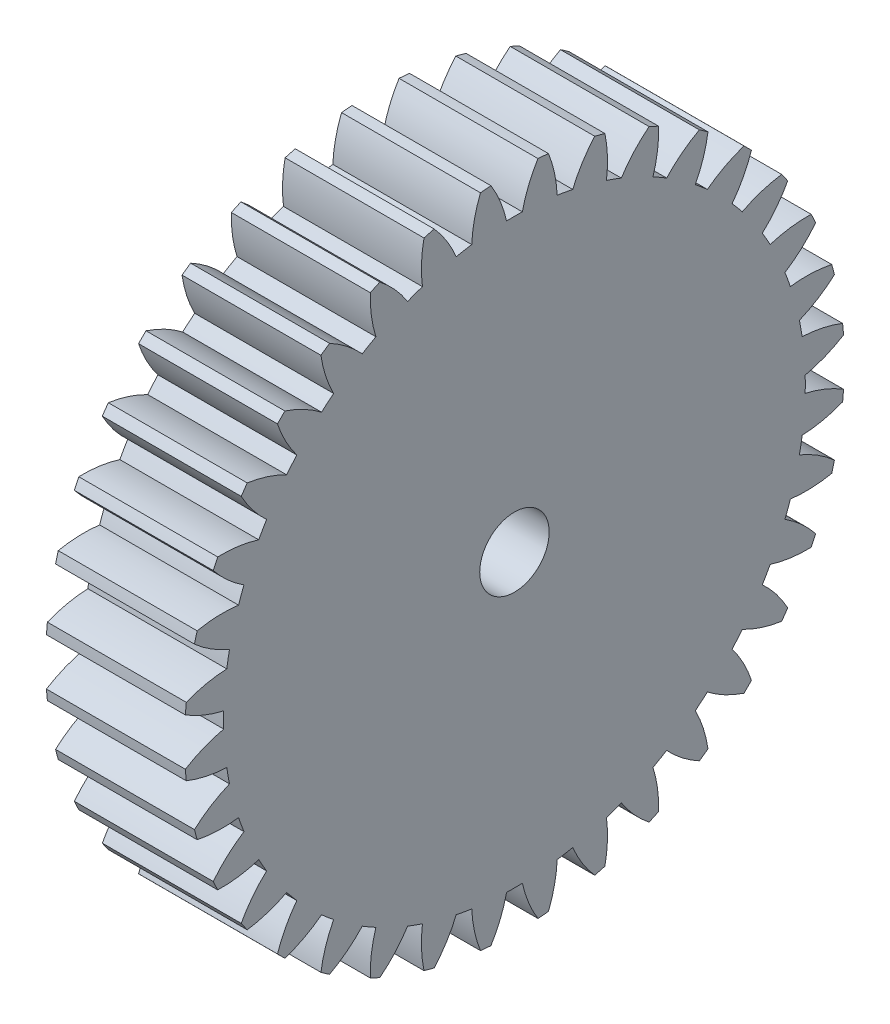
SolidWorks part; units mm, degrees
ref_plane "Plane1" through (0, 0, 0) normal (0, 0, 1) x (1, 0, 0)
ref_plane "Plane2" through (0, 0, 0) normal (0, 1, 0) x (1, 0, 0)
ref_plane "Plane3" through (0, 0, 0) normal (1, 0, 0) x (0, 0, -1)
other "Configuration Table"
sketch "HoldingSke" plane through (0, 0, 0) normal (0, 1, 0) x (1, 0, 0)
  line L0 (0, 0) -> (0.809, -0.5878)
  line L1 (-15, 0) -> (100, 0) construction
  line L2 (0, 0) -> (-2.1039, 2.3779)
  line L3 (0, 0) -> (-11.863, 4.5341)
  line L4 (0, 0) -> (6.9867, 5.0761)
  line L5 (0, 0) -> (-46.8476, -17.4728)
  line L6 (0, 0) -> (-6.6317, -4.4744)
  line L7 (-2.1039, 2.3779) -> (8.6586, 51.2059)
  line L8 (-76.2, 54.61) -> (-75.5, 54.61)
  line L9 (-71.009, 38.7566) -> (-53.1078, 45.2721)
  line L10 (-76.2, 71.12) -> (104.1128, 71.12)
  line L11 (0, 0) -> (-8, 0)
  line L12 (-76.2, 101.6) -> (-76.162, 101.6)
  line L13 (24.9733, 27.94) -> (52.9518, 28.4284)
  line L14 (24.9733, 27.94) -> (24.9743, 27.94)
  line L15 (24.9733, 27.94) -> (100.4006, 29.5858)
  line L16 (-63.627, -1) -> (-12.827, -1)
  circle A0 centre (0, 0) radius 2
  circle A1 centre (0, 0) radius 16.749
  circle A2 centre (0, 0) radius 37.5
  circle A3 centre (0, 0) radius 2
  dimension "MHD" = 33.498
  dimension "Hub_dia" = 75
  dimension "Bore" = 4
  dimension "MBD" = 4
  dimension "Num_teeth" = 36
  dimension "Pitch" = 1
  dimension "Overall_len" = 50
  dimension "Show_teeth" = 36
  dimension "Thickness" = 8
  dimension "OAL" = 50.0001
  dimension "T_dim" = 0.7
  dimension "Ap" = 20
  dimension "H" = 19.05
  dimension "Pitch_radius" = 180.3128
  dimension "Width" = 8
  dimension "Backlash" = 0.038
  dimension "Addendum_fac" = 1
  dimension "Dedendum_fac" = 1.25
  dimension "Clearance_fac" = 0.25
  dimension "Dedendum_add" = 0.001
  dimension "Module" = 1
sketch "BasProSke" plane through (0, 0, 0) normal (0, 1, 0) x (1, 0, 0)
  line L0 (-10, 0) -> (60, 0) construction
  line L1 (0, 0) -> (0, 19)
  line L2 (0, 0) -> (8, 0)
  line L3 (8, 0) -> (8, 19)
  line L4 (8, 19) -> (0, 19)
  dimension "Thickness" = 8
  dimension "Diameter" = 38
revolve "Base-Revolve" add sketch "BasProSke" angle 360 about L0
sketch "TooCutSke" plane through (0, 0, 0) normal (1, 0, 0) x (0, 0, -1)
  line L1 (0, 0) -> (0, 107) construction
  line L2 (0, 0) -> (-0.8516, 17.9798) construction
  line L3 (0, 0) -> (-3.1351, 35.8344) construction
  line L4 (-0.8516, 17.9798) -> (-1.5676, 17.9172) construction
  arc A0 (0.4547, 16.7428) -> (-0.4547, 16.7428) centre (0, 0) ccw
  arc A1 (1.3689, 18.9761) -> (-1.3689, 18.9761) centre (0, 0) ccw
  circle A2 centre (0, 0) radius 18 construction
  circle A3 centre (0, 0) radius 16.9145 construction
  arc A4 (-0.4547, 16.7428) -> (-1.3689, 18.9761) centre (-7.4808, 15.1702) ccw
  arc A5 (1.3689, 18.9761) -> (0.4547, 16.7428) centre (7.4808, 15.1702) ccw
  dimension "Root_dia" = 33.498
  dimension "Overcut_dia" = 38.0508
  dimension "Pitch_dia" = 36
  dimension "Base_dia" = 33.8289
  dimension "Flank_rad" = 7.2
  dimension "Half_ang" = 5
  dimension "Half_CT" = 0.7186
extrude "ToothCut" cut sketch "TooCutSke" along normal through all
fillet "Breaks" [suppressed] radius 0.02
fillet "RootFillets" [suppressed] radius 0.251
pattern_circular "TeethCuts" count 36 every 10 about axis through (-10, 0, 0) along (1, 0, 0) of "ToothCut", "RootFillets", "Breaks"
sketch "HubNeaOneSke" plane through (0, 0, 0) normal (-1, 0, 0) x (0, 0, 1)
  circle A0 centre (0, 0) radius 16.749
  dimension "Diameter" = 33.498
extrude "HubNearOne" [suppressed] add sketch "HubNeaOneSke" along normal blind 42.0001
sketch "HubNeaBotSke" plane through (0, 0, 0) normal (-1, 0, 0) x (0, 0, 1)
  circle A0 centre (0, 0) radius 16.749
  dimension "Diameter" = 33.498
extrude "HubNearBoth" [suppressed] add sketch "HubNeaBotSke" along normal blind 21
ref_plane "FarPln" through (8, 0, 0) normal (1, 0, 0) x (0, 0, -1)
sketch "HubFarSke" plane through (8, 0, 0) normal (1, 0, 0) x (0, 0, -1)
  circle A0 centre (0, 0) radius 16.749
  dimension "Diameter" = 33.498
extrude "HubFar" [suppressed] add sketch "HubFarSke" along normal blind 21
sketch "BorSke" plane through (0, 0, 0) normal (1, 0, 0) x (0, 0, -1)
  circle A0 centre (0, 0) radius 2
  dimension "Diameter" = 4
extrude "Bore" cut sketch "BorSke" along normal mid plane 100.0001
sketch "KeySke" plane through (0, 0, 0) normal (1, 0, 0) x (0, 0, -1)
  line L0 (-0.8, 0) -> (-0.8, 2.7)
  line L1 (-0.8, 2.7) -> (0.8, 2.7)
  line L2 (0.8, 2.7) -> (0.8, 0)
  line L3 (0, 0) -> (0, 34) construction
  line L4 (-0.8, 0) -> (0.8, 0)
  dimension "Offset" = 2.7
  dimension "Width" = 1.6
extrude "Keyway" [suppressed] cut sketch "KeySke" along normal mid plane 100.0001
pattern_circular "Keyway2" [suppressed] count 2 every 90 about axis through (-10, 0, 0) along (1, 0, 0)
equation "' \"Module@HoldingSke\" = 6.35"
equation "' \"Num_teeth@HoldingSke\" = 12"
equation "' \"Ap@HoldingSke\" =  20"
equation "' \"Ap@HoldingSke\" = 20"
equation "' \"Width@HoldingSke\" = 0.5 * 25.4"
equation "' \"Hub_dia@HoldingSke\"= 1 * 25.4"
equation "' \"Hub_dia@HoldingSke\" = 1 * 25.4"
equation "' \"Overall_len@HoldingSke\" = 1.0 * 25.4"
equation "' \"Bore@HoldingSke\" = 0.75 * 25.4"
equation "' \"T_dim@HoldingSke\" = 0.1 * 25.4"
equation "' \"Width@KeySke\" = 0.25 * 25.4"
equation "' \"Show_teeth@HoldingSke\" = 13"
equation "' \"Backlash@HoldingSke\" = 0.009 * 25.4"
equation "' \"Addendum_fac@HoldingSke\" = 1.0"
equation "' \"Dedendum_fac@HoldingSke\" = 1.25"
equation "' \"Dedendum_add@HoldingSke\" = 0.00005 * 25.4"
equation "' \"Clearance_fac@HoldingSke\" = 0.25"
equation "\"Pitch@HoldingSke\" = 1 / \"Module@HoldingSke\""
equation "\"Overcut_dia@TooCutSke\" = (\"Num_teeth@HoldingSke\" + 2 * \"Addendum_fac@HoldingSke\") / \"Pitch@HoldingSke\" + 0.002 * 25.4"
equation "\"Pitch_dia@TooCutSke\" = \"Num_teeth@HoldingSke\" / \"Pitch@HoldingSke\""
equation "\"Base_dia@TooCutSke\" = \"Num_teeth@HoldingSke\" / \"Pitch@HoldingSke\" * cos((\"Ap@HoldingSke\"  * 3.14159265 / 180))"
equation "\"Root_dia@TooCutSke\" = (\"Num_teeth@HoldingSke\" + 2) / \"Pitch@HoldingSke\" - 2 * (\"Addendum_fac@HoldingSke\" + \"Dedendum_fac@HoldingSke\") / \"Pitch@HoldingSke\" - \"Dedendum_add@HoldingSke\" * 2"
equation "\"Half_ang@TooCutSke\" = 180 / \"Num_teeth@HoldingSke\""
equation "\"Half_CT@TooCutSke\" = \"Num_teeth@HoldingSke\" / \"Pitch@HoldingSke\" * sin((3.14159265 / 2 / \"Num_teeth@HoldingSke\")) / 2 - 7 * \"Backlash@HoldingSke\" / 4"
equation "\"Flank_rad@TooCutSke\" = \"Num_teeth@HoldingSke\" / \"Pitch@HoldingSke\" / 5"
equation "\"Radius@RootFillets\" = \"Clearance_fac@HoldingSke\" / \"Pitch@HoldingSke\" + \"Dedendum_add@HoldingSke\""
equation "\"Break_rad@Breaks\" = 0.02 / \"Pitch@HoldingSke\""
equation "\"Thickness@HoldingSke\" = \"Width@HoldingSke\""
equation "\"OAL@HoldingSke\" = \"Thickness@HoldingSke\""
equation "\"MHD@HoldingSke\" = (\"Num_teeth@HoldingSke\" + 2) / \"Pitch@HoldingSke\" - 2 * (\"Addendum_fac@HoldingSke\" + \"Dedendum_fac@HoldingSke\")  / \"Pitch@HoldingSke\" - \"Dedendum_add@HoldingSke\" * 2"
equation "\"MBD@HoldingSke\" = (\"Num_teeth@HoldingSke\" + 2) / \"Pitch@HoldingSke\" - 2 * (\"Addendum_fac@HoldingSke\" + \"Dedendum_fac@HoldingSke\")  / \"Pitch@HoldingSke\" - \"Dedendum_add@HoldingSke\" * 2 - 0.002 * 25.4"
equation "\"MHD@HoldingSke\" = ((sgn( \"MHD@HoldingSke\" - \"Hub_dia@HoldingSke\" )-1)*( \"MHD@HoldingSke\" - \"Hub_dia@HoldingSke\" ))/-2+ \"Hub_dia@HoldingSke\""
equation "\"MBD@HoldingSke\" = ((sgn( \"MBD@HoldingSke\" - \"Bore@HoldingSke\" )-1)*( \"MBD@HoldingSke\" - \"Bore@HoldingSke\" ))/-2+ \"Bore@HoldingSke\""
equation "\"OAL@HoldingSke\" = ((sgn( \"OAL@HoldingSke\" - \"Overall_len@HoldingSke\" )+1)*( \"OAL@HoldingSke\" - \"Overall_len@HoldingSke\" ))/2 + \"Overall_len@HoldingSke\" + 0.000002 * 25.4"
equation "\"Num_teeth@TeethCuts\" = int( \"Show_teeth@HoldingSke\" ) + 1"
equation "\"Num_teeth@TeethCuts\" = ((sgn( \"Num_teeth@TeethCuts\" - \"Num_teeth@HoldingSke\" )-1)*( \"Num_teeth@TeethCuts\" - \"Num_teeth@HoldingSke\" ))/-2+ \"Num_teeth@HoldingSke\""
equation "\"Num_teeth@TeethCuts\" = ((sgn( \"Num_teeth@TeethCuts\" - 2.0)+1)*( \"Num_teeth@TeethCuts\" - 2.0))/2 +2.0"
equation "\"Angle@TeethCuts\" = 360.0 / \"Num_teeth@HoldingSke\""
equation "\"Diameter@BasProSke\" = (\"Num_teeth@HoldingSke\" + 2 * \"Addendum_fac@HoldingSke\") / \"Pitch@HoldingSke\""
equation "\"Thickness@BasProSke\"  = \"Thickness@HoldingSke\""
equation "' \"Fillet_rad@BasProSke\" =  \"Thickness@HoldingSke\" * 0.05"
equation "' \"Fillet_rad@BasProSke\" = \"Thickness@HoldingSke\" * 0.05"
equation "\"MHD@HoldingSke\" = ((sgn( \"MHD@HoldingSke\" - \"Root_dia@TooCutSke\" )-1)*( \"MHD@HoldingSke\" - \"Root_dia@TooCutSke\" ))/-2+ \"Root_dia@TooCutSke\""
equation "\"Diameter@HubNeaOneSke\" = \"MHD@HoldingSke\""
equation "\"Length@HubNearOne\" = \"OAL@HoldingSke\" - \"Thickness@BasProSke\""
equation "\"Diameter@HubNeaBotSke\" = \"MHD@HoldingSke\""
equation "\"Length@HubNearBoth\" = ( \"OAL@HoldingSke\" - \"Thickness@BasProSke\" ) / 2.0"
equation "\"Thickness@FarPln\" = \"Thickness@BasProSke\""
equation "\"Diameter@HubFarSke\" = \"MHD@HoldingSke\""
equation "\"Length@HubFar\" = ( \"OAL@HoldingSke\" - \"Thickness@BasProSke\" ) / 2.0"
equation "\"Diameter@BorSke\" = \"MBD@HoldingSke\""
equation "\"D1@Bore\" = \"OAL@HoldingSke\" * 2.0"
equation "\"D1@Keyway\" = \"OAL@HoldingSke\" * 2.0"
equation "\"Offset@KeySke\" = \"T_dim@HoldingSke\" + \"MBD@HoldingSke\" / 2.0"
